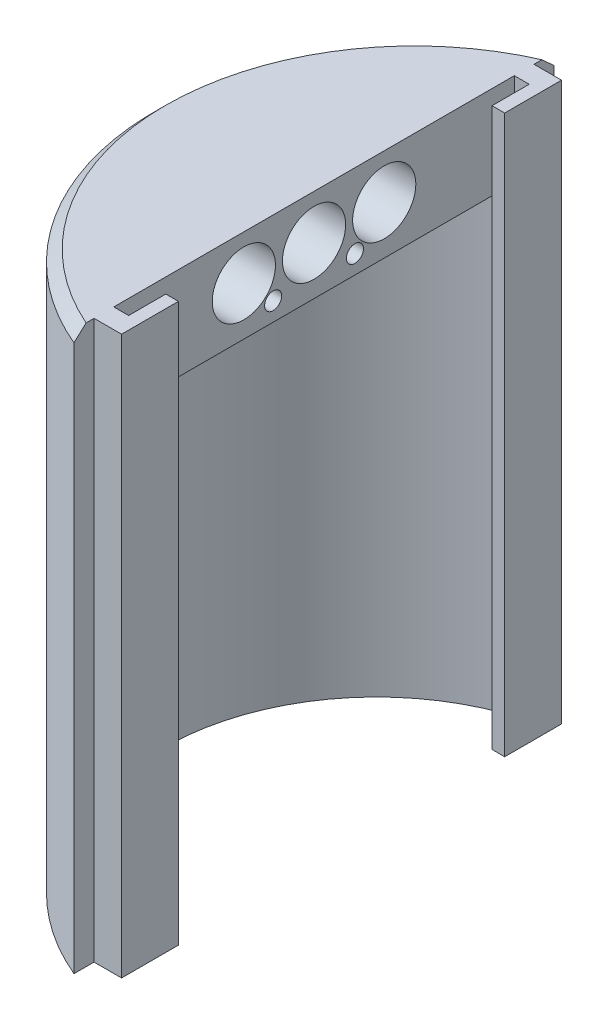
SolidWorks part; units mm, degrees
ref_plane "Plan de face" through (0, 0, 0) normal (0, 0, 1) x (1, 0, 0)
ref_plane "Plan de dessus" through (0, 0, 0) normal (0, 1, 0) x (1, 0, 0)
ref_plane "Plan de droite" through (0, 0, 0) normal (1, 0, 0) x (0, 0, -1)
sketch "Esquisse1" plane through (0, 0, 0) normal (0, 1, 0) x (1, 0, 0)
  circle A0 centre (0, 0) radius 70
  dimension "D1" = 140
extrude "Boss.-Extru.1" add sketch "Esquisse1" against normal blind 150
sketch "Esquisse2" plane through (0, 0, 0) normal (0, 1, 0) x (1, 0, 0)
  line L0 (0, 70) -> (0, -70) construction
  line L1 (-16, 68.1469) -> (-16, 62.9469)
  line L2 (-16, 62.9469) -> (-8, 62.9469)
  line L3 (-8, 62.9469) -> (-8, 47.7469)
  line L4 (-8, 47.7469) -> (-12.8, 47.7469)
  line L5 (-12.8, 47.7469) -> (-12.8, 57.4469)
  line L6 (-12.8, 57.4469) -> (-16, 57.4469)
  line L7 (-16, -62.9469) -> (-8, -62.9469)
  line L8 (-8, -62.9469) -> (-8, -48.0469)
  line L9 (-8, -48.0469) -> (-12.8, -48.0469)
  line L10 (-12.8, -48.0469) -> (-12.8, -57.7469)
  line L11 (-12.8, -57.7469) -> (-16, -57.7469)
  line L12 (-16, -62.9469) -> (-16, -68.1469)
  line L13 (-16, 57.4469) -> (-16, -57.7469)
  circle A0 centre (0, 0) radius 70 construction
  arc A1 (-16, 68.1469) -> (-16, -68.1469) centre (0, 0) cw
  dimension "D2" = 70
  dimension "D3" = 5.2
  dimension "D1" = 16
  dimension "D4" = 5.5
  dimension "D5" = 3.2
  dimension "D6" = 8
  dimension "D7" = 5.2
  dimension "D8" = 3.2
  dimension "D9" = 9.7
  dimension "D10" = 9.7
  dimension "D11" = 8
  dimension "D12" = 5.2
extrude "Enlèv. mat.-Extru.1" cut sketch "Esquisse2" against normal blind 150
sketch "Esquisse3" plane through (0, 0, 0) normal (0, 1, 0) x (1, 0, 0)
  line L0 (-27, 64.5833) -> (-27, 59.1833)
  line L1 (-16, 68.1469) -> (-16, 62.9469) construction
  line L2 (-27, 59.1833) -> (-19.6, 59.1833)
  line L3 (-19.6, 59.1833) -> (-19.6, 43.8833)
  line L4 (-19.6, 43.8833) -> (-23, 43.8833)
  line L5 (-23, 43.8833) -> (-23, 53.8833)
  line L6 (-23, 53.8833) -> (-27, 53.8833)
  line L7 (-27, -59.1833) -> (-19.6, -59.1833)
  line L8 (-19.6, -59.1833) -> (-19.6, -43.8833)
  line L9 (-19.6, -43.8833) -> (-23, -43.8833)
  line L10 (-23, -43.8833) -> (-23, -53.8833)
  line L11 (-23, -53.8833) -> (-27, -53.8833)
  line L12 (-27, 53.8833) -> (-27, -53.8833)
  line L13 (-27, -59.1833) -> (-27, -64.5833)
  arc A0 (-16, 68.1469) -> (-16, -68.1469) centre (0, 0) ccw construction
  dimension "D1" = 11
  dimension "D2" = 5.4
  dimension "D3" = 5.3
  dimension "D4" = 4
  dimension "D5" = 7.4
  dimension "D6" = 10
  dimension "D7" = 5.4
  dimension "D8" = 5.3
  dimension "D9" = 4
  dimension "D10" = 7.4
  dimension "D11" = 10
extrude "Enlèv. mat.-Extru.2" cut sketch "Esquisse3" against normal through all
sketch "Esquisse4" plane through (-27, 0, 0) normal (1, 0, 0) x (0, 0, -1)
  line L2 (34.1, 0) -> (-34.1, 0) construction
  line L3 (0, 0) -> (0, -58.7793) construction
  circle A0 centre (-11, -20) radius 2.3
  circle A1 centre (11, -20) radius 2.3
  dimension "D3" = 4.6
  dimension "D4" = 4.6
  dimension "D1" = 11
  dimension "D2" = 11
  dimension "D5" = 20
  dimension "D6" = 20
extrude "Enlèv. mat.-Extru.3" cut sketch "Esquisse4" against normal blind 20
sketch "Esquisse5" plane through (0, -150, 0) normal (0, -1, 0) x (1, 0, 0)
  line L0 (-27, 53.8833) -> (-27, -53.8833)
  line L1 (-27, 53.8833) -> (-30, 53.8833)
  line L2 (-27, -53.8833) -> (-30, -53.8833)
  arc A1 (-30, -53.8833) -> (-30, 53.8833) centre (-10.1671, 0) cw
  arc A2 (-27, 64.5833) -> (-27, -64.5833) centre (0, 0) ccw construction
  dimension "D3" = 10.1671
  dimension "D1" = 3
  dimension "D2" = 3
extrude "Enlèv. mat.-Extru.4" cut sketch "Esquisse5" against normal blind 125
chamfer "Chanfrein1" distance 3 angle 45 1 edges at (-70, 0, 0)
sketch "Esquisse6" plane through (-27, 0, 0) normal (1, 0, 0) x (0, 0, -1)
  line L1 (27.72, 0) -> (-27.72, 0) construction
  line L2 (-53.8833, 0) -> (-53.8833, -25) construction
  line L4 (53.8833, 0) -> (53.8833, -25) construction
  circle A0 centre (-18.8833, -12) radius 8.5
  circle A1 centre (18.8833, -12) radius 8.5
  circle A2 centre (-0.0033, -12) radius 8.5
  dimension "D1" = 17
  dimension "D2" = 17
  dimension "D3" = 17
  dimension "D4" = 12
  dimension "D5" = 12
  dimension "D6" = 12
  dimension "D7" = 53.88
  dimension "D8" = 35
  dimension "D9" = 35
extrude "Enlèv. mat.-Extru.5" cut sketch "Esquisse6" against normal blind 50
